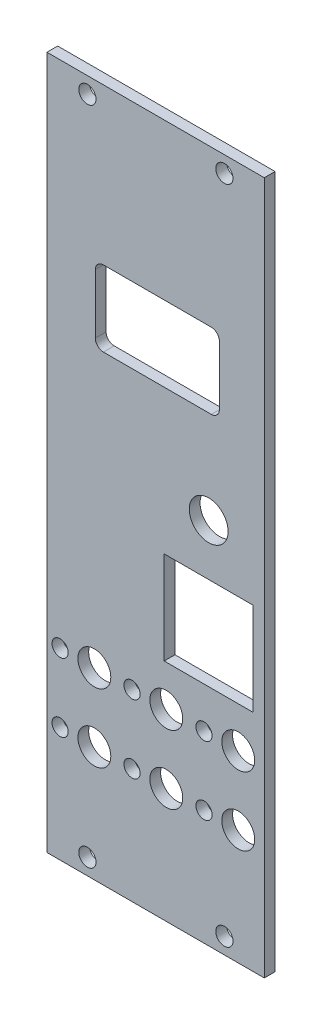
SolidWorks part; units mm, degrees
ref_plane "Front Plane" through (0, 0, 0) normal (0, 0, 1) x (1, 0, 0)
ref_plane "Top Plane" through (0, 0, 0) normal (0, 1, 0) x (1, 0, 0)
ref_plane "Right Plane" through (0, 0, 0) normal (1, 0, 0) x (0, 0, -1)
sketch "Sketch2" plane through (0, 0, 0) normal (0, 0, 1) x (1, 0, 0)
  line L0 (20.15, 128.5) -> (20.15, 0) construction
  line L1 (0, 0) -> (40.3, 0)
  line L2 (0, 0) -> (0, 128.5)
  line L3 (0, 128.5) -> (40.3, 128.5)
  line L4 (40.3, 0) -> (40.3, 128.5)
  line L5 (29.99, 58.82) -> (29.99, 41.62) construction
  line L6 (0.15, 15) -> (40.15, 15) construction
  line L7 (0.15, 15) -> (0.15, 105.95) construction
  line L8 (0.15, 105.95) -> (40.15, 105.95) construction
  line L9 (40.15, 15) -> (40.15, 105.95) construction
  line L10 (0.15, 15) -> (40.15, 105.95) construction
  line L11 (0.15, 105.95) -> (40.15, 15) construction
  line L12 (21.74, 58.82) -> (38.24, 58.82)
  line L13 (21.74, 58.82) -> (21.74, 41.62)
  line L14 (21.74, 41.62) -> (38.24, 41.62)
  line L15 (38.24, 58.82) -> (38.24, 41.62)
  line L16 (21.74, 53.1) -> (38.24, 53.1) construction
  line L17 (20.47, 99.59) -> (20.47, 85.59) construction
  line L18 (10.47, 99.59) -> (30.47, 99.59)
  line L19 (8.97, 98.09) -> (8.97, 87.09)
  line L20 (10.47, 85.59) -> (30.47, 85.59)
  line L21 (31.97, 98.09) -> (31.97, 87.09)
  line L22 (6.815, 105.31) -> (34.125, 105.31) construction
  line L23 (6.815, 105.31) -> (6.815, 77.37) construction
  line L24 (6.815, 77.37) -> (34.125, 77.37) construction
  line L25 (34.125, 105.31) -> (34.125, 77.37) construction
  line L26 (20.47, 105.31) -> (20.47, 77.37) construction
  line L27 (8.97, 92.59) -> (31.97, 92.59) construction
  line L28 (6.815, 91.34) -> (34.125, 91.34) construction
  circle A0 centre (7.5, 125.5) radius 1.6
  circle A1 centre (32.9, 125.5) radius 1.6
  circle A2 centre (7.5, 3) radius 1.6
  circle A3 centre (32.9, 3) radius 1.6
  circle A4 centre (8.79, 34.05) radius 3.05
  circle A5 centre (8.79, 21.35) radius 3.05
  circle A6 centre (22.13, 34.05) radius 3.05
  circle A7 centre (22.13, 21.35) radius 3.05
  circle A8 centre (35.47, 21.35) radius 3.05
  circle A9 centre (35.47, 34.05) radius 3.05
  circle A10 centre (2.44, 34.05) radius 1.5
  circle A11 centre (15.78, 34.05) radius 1.5
  circle A12 centre (29.12, 34.05) radius 1.5
  circle A13 centre (2.44, 21.35) radius 1.5
  circle A14 centre (15.78, 21.35) radius 1.5
  circle A15 centre (29.12, 21.35) radius 1.5
  circle A16 centre (29.99, 68.34) radius 3.6
  arc A17 (8.97, 87.09) -> (10.47, 85.59) centre (10.47, 87.09) ccw
  arc A18 (10.47, 99.59) -> (8.97, 98.09) centre (10.47, 98.09) ccw
  arc A19 (30.47, 99.59) -> (31.97, 98.09) centre (30.47, 98.09) cw
  arc A20 (30.47, 85.59) -> (31.97, 87.09) centre (30.47, 87.09) ccw
  point P7 (20.15, 60.475)
  point P54 (29.99, 53.1)
  point P61 (8.97, 85.59)
  point P64 (8.97, 99.59)
  point P67 (31.97, 99.59)
  dimension "D6" = 3.2
  dimension "D15" = 8.64
  dimension "D22" = 6.1
  dimension "D28" = 3
  dimension "D35" = 34.29
  dimension "D37" = 7.2
  dimension "D45" = 1.5
  dimension "D49" = 20.32
  dimension "D1" = 40.3
  dimension "D2" = 128.5
  dimension "D3" = 40
  dimension "D4" = 90.95
  dimension "D5" = 15
  dimension "D7" = 3
  dimension "D8" = 3
  dimension "D9" = 7.5
  dimension "D10" = 3
  dimension "D11" = 7.5
  dimension "D12" = 3
  dimension "D13" = 25.4
  dimension "D14" = 25.4
  dimension "D16" = 8.64
  dimension "D17" = 12.7
  dimension "D18" = 12.7
  dimension "D19" = 12.7
  dimension "D20" = 13.34
  dimension "D21" = 13.34
  dimension "D23" = 6.35
  dimension "D24" = 6.35
  dimension "D25" = 6.35
  dimension "D26" = 13.34
  dimension "D27" = 13.34
  dimension "D29" = 6.35
  dimension "D30" = 6.35
  dimension "D31" = 6.35
  dimension "D32" = 6.35
  dimension "D33" = 6.35
  dimension "D34" = 6.35
  dimension "D36" = 10.16
  dimension "D38" = 16.5
  dimension "D39" = 17.2
  dimension "D40" = 5.72
  dimension "D41" = 10.16
  dimension "D42" = 15.24
  dimension "D43" = 23
  dimension "D44" = 14
  dimension "D46" = 5.72
  dimension "D47" = 27.94
  dimension "D48" = 27.31
  dimension "D50" = 14.61
extrude "Boss-Extrude2" add sketch "Sketch2" along normal blind 2
sketch "Sketch3" plane through (0, 0, 2) normal (0, 0, 1) x (1, 0, 0)
  text T0 "CS:GO GSI\r\nINTERFACE"
